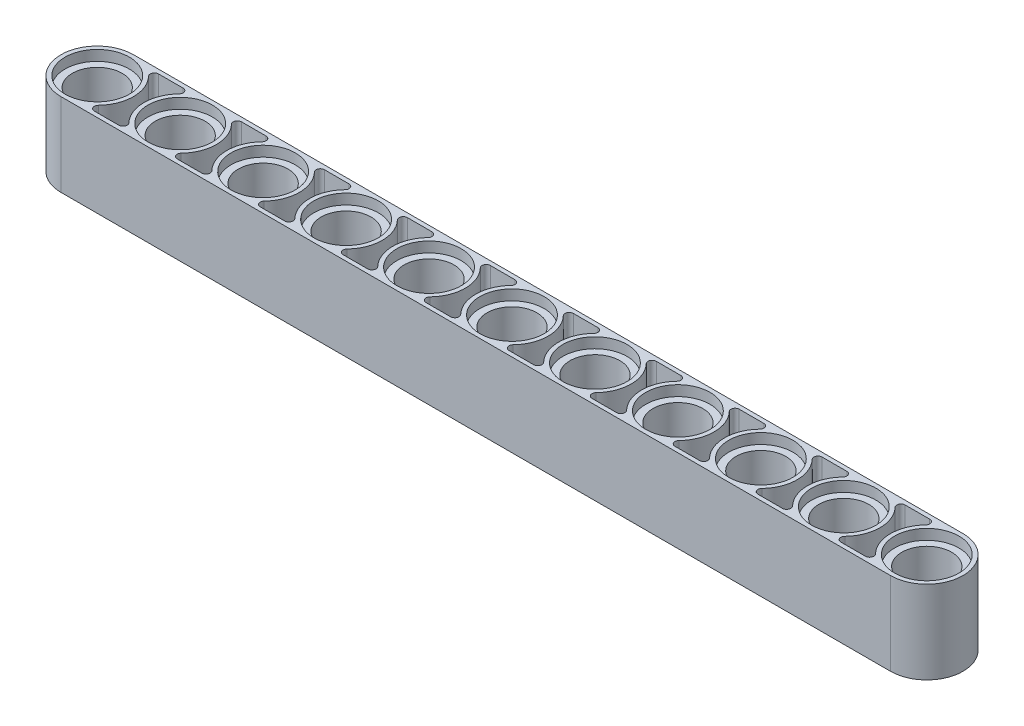
SolidWorks part; units mm, degrees
ref_plane "Front Plane" through (0, 0, 0) normal (0, 0, 1) x (1, 0, 0)
ref_plane "Top Plane" through (0, 0, 0) normal (0, 1, 0) x (1, 0, 0)
ref_plane "Right Plane" through (0, 0, 0) normal (1, 0, 0) x (0, 0, -1)
sketch "Sketch1" plane through (0, 0, 0) normal (0, 1, 0) x (1, 0, 0)
  line L0 (0, 0) -> (80, 0) construction
  line L1 (0, 3.5) -> (80, 3.5)
  line L2 (0, -3.5) -> (80, -3.5)
  arc A0 (0, 3.5) -> (0, -3.5) centre (0, 0) ccw
  arc A1 (80, -3.5) -> (80, 3.5) centre (80, 0) ccw
  point P3 (40, 0)
  point P8 (-3.5, 0)
  point P9 (83.5, 0)
  dimension "D1" = 87
  dimension "D2" = 7
extrude "Boss-Extrude1" add sketch "Sketch1" along normal mid plane 8
sketch "Sketch2" plane through (0, 4, 0) normal (0, 1, 0) x (1, 0, 0)
  circle A0 centre (0, 0) radius 3.1
  dimension "D1" = 6.2
extrude "Cut-Extrude1" cut sketch "Sketch2" against normal blind 1
sketch "Sketch3" plane through (0, -4, 0) normal (0, -1, 0) x (-1, 0, 0)
  circle A0 centre (0, 0) radius 3.1
  dimension "D1" = 6.2
extrude "Cut-Extrude2" cut sketch "Sketch3" against normal blind 1
sketch "Sketch4" plane through (0, 0, 0) normal (0, 1, 0) x (1, 0, 0)
  circle A0 centre (0, 0) radius 2.4
  dimension "D1" = 4.8
extrude "Cut-Extrude3" cut sketch "Sketch4" against normal through all both and the other way through all
pattern_linear "LPattern1" count 11 spacing 8 along (1, 0, 0) of "Cut-Extrude2", "Cut-Extrude1", "Cut-Extrude3"
sketch "Sketch5" plane through (0, 0, 0) normal (0, 1, 0) x (1, 0, 0)
  line L0 (2.8142, 3.1) -> (5.1858, 3.1)
  line L1 (2.8142, -3.1) -> (5.1858, -3.1)
  arc A0 (2.5256, -2.4231) -> (2.5256, 2.4231) centre (0, 0) ccw
  arc A1 (5.4744, 2.4231) -> (5.4744, -2.4231) centre (8, 0) ccw
  arc A6 (2.5256, -2.4231) -> (2.8142, -3.1) centre (2.8142, -2.7) ccw
  arc A7 (5.1858, -3.1) -> (5.4744, -2.4231) centre (5.1858, -2.7) ccw
  arc A8 (5.4744, 2.4231) -> (5.1858, 3.1) centre (5.1858, 2.7) ccw
  arc A9 (2.8142, 3.1) -> (2.5256, 2.4231) centre (2.8142, 2.7) ccw
  dimension "D1" = 7
  dimension "D2" = 7
  dimension "D3" = 0.4
extrude "Cut-Extrude4" cut sketch "Sketch5" against normal through all both and the other way through all
pattern_linear "LPattern2" count 10 spacing 8 along (1, 0, 0) of "Cut-Extrude4"
